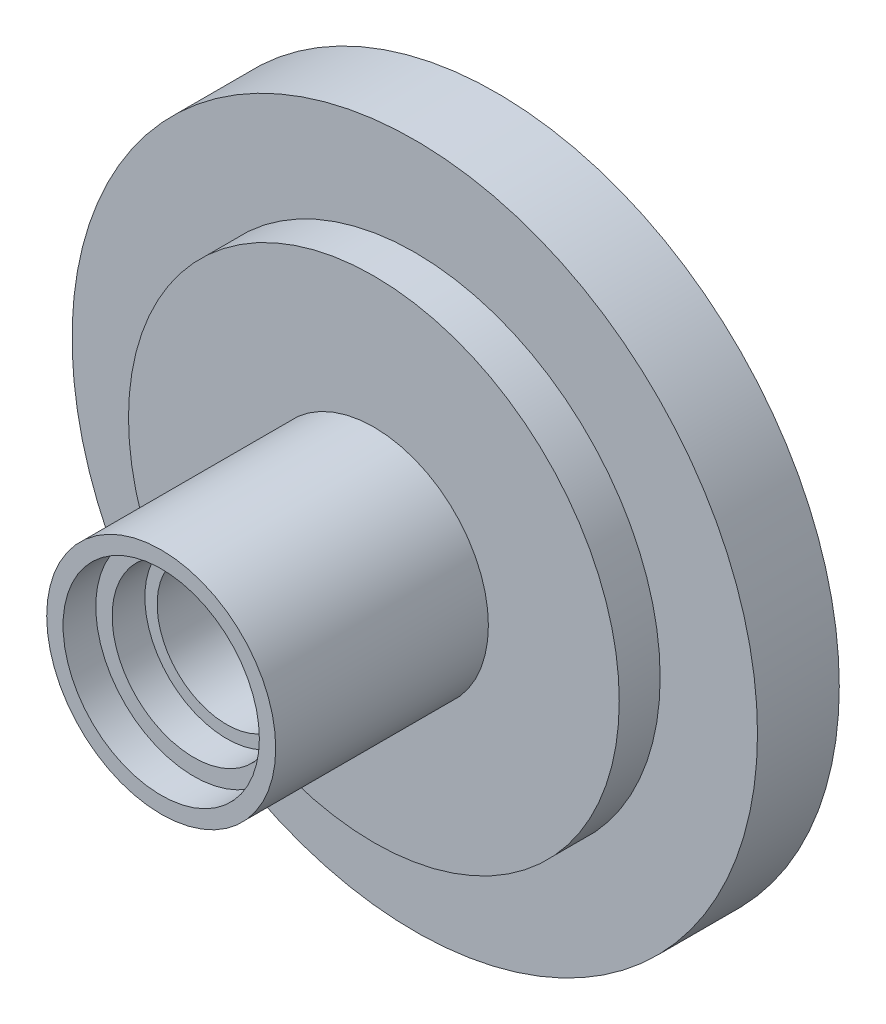
SolidWorks part; units mm, degrees
material "AISI 304"
ref_plane "Front" through (0, 0, 0) normal (0, 0, 1) x (1, 0, 0)
ref_plane "Top" through (0, 0, 0) normal (0, 1, 0) x (1, 0, 0)
ref_plane "Right" through (0, 0, 0) normal (1, 0, 0) x (0, 0, -1)
sketch "Sketch1" plane through (0, 0, 0) normal (1, 0, 0) x (0, 0, -1)
  line L0 (0, 6) -> (0, 7)
  line L1 (13, 15) -> (15.5, 15)
  line L2 (15.5, 15) -> (15.5, 20.95)
  line L3 (15.5, 20.95) -> (20.5, 20.95)
  line L4 (20.5, 20.95) -> (20.5, 7)
  line L5 (20.5, 7) -> (28, 7)
  line L6 (28, 7) -> (28, 6)
  line L7 (24, 4.25) -> (4, 4.25)
  line L8 (0, 0) -> (20, 0) construction
  line L13 (0, 7) -> (13, 7)
  line L14 (13, 7) -> (13, 15)
  line L15 (24, 4.25) -> (24, 5)
  line L16 (24, 5) -> (26, 5)
  line L17 (26, 5) -> (26, 6)
  line L18 (26, 6) -> (28, 6)
  line L19 (0, 6) -> (2, 6)
  line L20 (2, 6) -> (2, 5)
  line L21 (2, 5) -> (4, 5)
  line L22 (4, 5) -> (4, 4.25)
  point P11 (15.5, 17.975)
  point P18 (4, 4.625)
  dimension "D1" = 28
  dimension "D2" = 7.5
  dimension "D3" = 5
  dimension "D4" = 8.5
  dimension "D5" = 30
  dimension "D6" = 41.9
  dimension "D7" = 14
  dimension "D8" = 10
  dimension "D9" = 12
  dimension "D10" = 2
  dimension "D11" = 2
  dimension "D12" = 2.5
  dimension "D13" = 2
  dimension "D14" = 2
  dimension "D15" = 12
  dimension "D16" = 10
revolve "Revolve1" add sketch "Sketch1" angle 360 about L8
